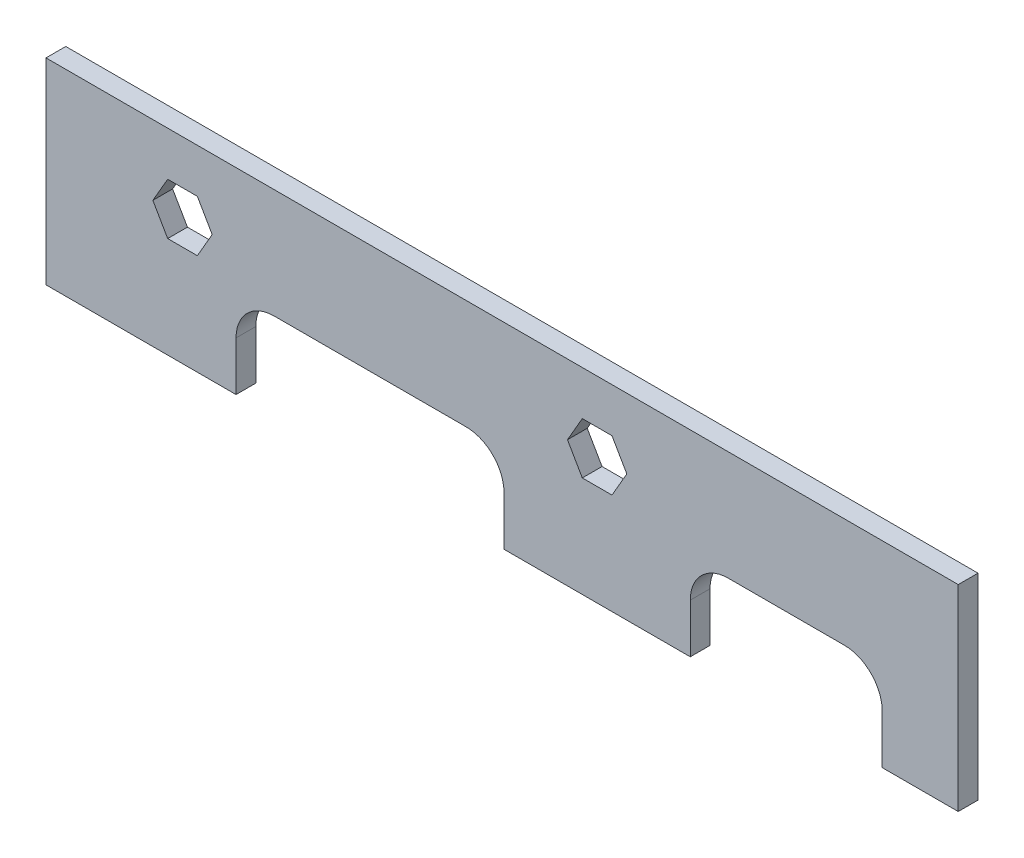
SolidWorks part; units mm, degrees
ref_plane "Front Plane" through (0, 0, 0) normal (0, 0, 1) x (1, 0, 0)
ref_plane "Top Plane" through (0, 0, 0) normal (0, 1, 0) x (1, 0, 0)
ref_plane "Right Plane" through (0, 0, 0) normal (1, 0, 0) x (0, 0, -1)
sketch "Sketch1" plane through (0, 0, 0) normal (0, 0, 1) x (1, 0, 0)
  line L0 (8750.1853, 2968.4132) -> (8597.7853, 2968.4132)
  line L1 (8731.1353, 2950.1252) -> (8711.7678, 2950.1252)
  line L2 (8667.9528, 2950.1252) -> (8635.8853, 2950.1252)
  line L3 (8597.7853, 2968.4132) -> (8597.7853, 2935.5735)
  line L4 (8750.1853, 2968.4132) -> (8750.1853, 2935.5735)
  line L5 (8629.5353, 2943.7752) -> (8629.5353, 2935.5735)
  line L6 (8674.3028, 2935.5735) -> (8674.3028, 2943.7752)
  line L7 (8705.4178, 2943.7752) -> (8705.4178, 2935.5735)
  line L8 (8737.4853, 2943.7752) -> (8737.4853, 2935.5735)
  line L9 (8618.1147, 2961.0218) -> (8615.6363, 2956.7292)
  line L10 (8615.6363, 2956.7292) -> (8618.1147, 2952.4366)
  line L11 (8618.1147, 2952.4366) -> (8623.0713, 2952.4366)
  line L12 (8623.0713, 2952.4366) -> (8625.5497, 2956.7292)
  line L13 (8625.5497, 2956.7292) -> (8623.0713, 2961.0218)
  line L14 (8623.0713, 2961.0218) -> (8618.1147, 2961.0218)
  line L15 (8687.382, 2961.0218) -> (8684.9036, 2956.7292)
  line L16 (8684.9036, 2956.7292) -> (8687.382, 2952.4366)
  line L17 (8687.382, 2952.4366) -> (8692.3386, 2952.4366)
  line L18 (8692.3386, 2952.4366) -> (8694.817, 2956.7292)
  line L19 (8694.817, 2956.7292) -> (8692.3386, 2961.0218)
  line L20 (8692.3386, 2961.0218) -> (8687.382, 2961.0218)
  line L21 (8597.7853, 2935.5735) -> (8629.5353, 2935.5735)
  line L22 (8674.3028, 2935.5735) -> (8705.4178, 2935.5735)
  line L23 (8737.4853, 2935.5735) -> (8750.1853, 2935.5735)
  arc A0 (8711.7678, 2950.1252) -> (8705.4178, 2943.7752) centre (8711.7678, 2943.7752) ccw
  arc A1 (8737.4853, 2943.7752) -> (8731.1353, 2950.1252) centre (8731.1353, 2943.7752) ccw
  arc A2 (8674.3028, 2943.7752) -> (8667.9528, 2950.1252) centre (8667.9528, 2943.7752) ccw
  arc A3 (8635.8853, 2950.1252) -> (8629.5353, 2943.7752) centre (8635.8853, 2943.7752) ccw
extrude "Boss-Extrude1" add sketch "Sketch1" along normal blind 3.302
